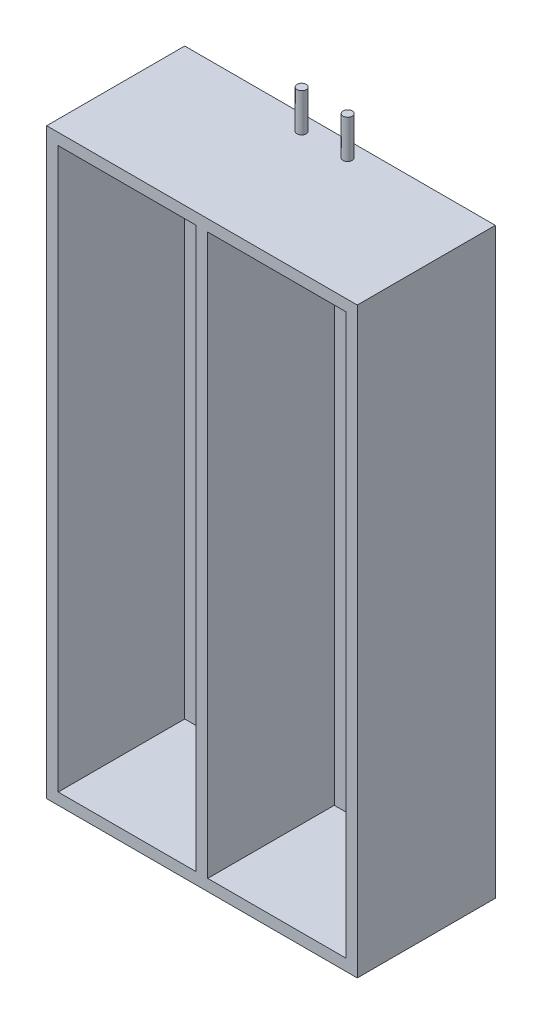
SolidWorks part; units mm, degrees
ref_plane "Front Plane" through (0, 0, 0) normal (1, 0, 0) x (0, 1, 0)
ref_plane "Top Plane" through (0, 0, 0) normal (0, 0, 1) x (0, 1, 0)
ref_plane "Right Plane" through (0, 0, 0) normal (0, 1, 0) x (-1, 0, 0)
sketch "Sketch1" plane through (0, 0, 0) normal (0, 0, 1) x (0, 1, 0)
  line L1 (-38, -20.25) -> (38, -20.25)
  line L2 (-38, -20.25) -> (-38, 20.25)
  line L3 (-38, 20.25) -> (38, 20.25)
  line L4 (38, -20.25) -> (38, 20.25)
  line L5 (-38, -20.25) -> (38, 20.25) construction
  line L6 (-38, 20.25) -> (38, -20.25) construction
  point P0 (0, 0)
  dimension "D1" = 76
  dimension "D2" = 40.5
extrude "Boss-Extrude1" add sketch "Sketch1" along normal mid plane 18
shell "Shell1" thickness 1.5
sketch "Sketch2" plane through (0, 0, -7.5) normal (0, 0, 1) x (1, 0, 0)
  line L0 (18.75, 36.5) -> (-18.75, 36.5) construction
  line L1 (0.75, 36.5) -> (-0.75, 36.5)
  line L2 (0.75, 36.5) -> (0.75, -36.5)
  line L3 (0.75, -36.5) -> (-0.75, -36.5)
  line L4 (-0.75, 36.5) -> (-0.75, -36.5)
  line L5 (-18.75, -36.5) -> (18.75, -36.5) construction
  dimension "D1" = 1.5
  dimension "D2" = 0.75
extrude "Boss-Extrude2" add sketch "Sketch2" along normal up to vertex (16.5 mm away)
sketch "Sketch3" plane through (0, 38, 0) normal (0, 1, 0) x (-1, 0, 0)
  line L0 (-20.25, -9) -> (20.25, -9) construction
  line L1 (0, 9.9) -> (0, -9.9) construction
  circle A0 centre (3, -7) radius 0.6
  circle A1 centre (-3, -7) radius 0.6
  dimension "D1" = 1.2
  dimension "D2" = 2
  dimension "D3" = 3
extrude "Boss-Extrude3" add sketch "Sketch3" along normal blind 5
